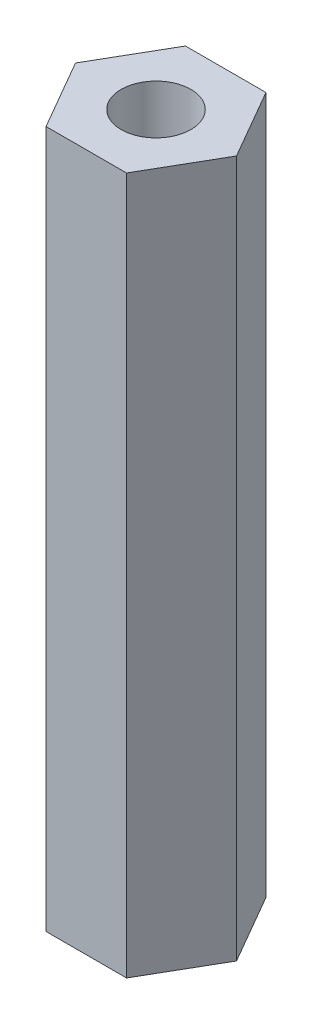
SolidWorks part; units mm, degrees
ref_plane "Front Plane" through (0, 0, 0) normal (0, 0, 1) x (1, 0, 0)
ref_plane "Top Plane" through (0, 0, 0) normal (0, 1, 0) x (1, 0, 0)
ref_plane "Right Plane" through (0, 0, 0) normal (1, 0, 0) x (0, 0, -1)
sketch "Sketch1" plane through (0, 0, 0) normal (0, 1, 0) x (1, 0, 0)
  line L1 (1.7321, 3) -> (-1.7321, 3)
  line L2 (-1.7321, 3) -> (-3.4641, 0)
  line L3 (-3.4641, 0) -> (-1.7321, -3)
  line L4 (-1.7321, -3) -> (1.7321, -3)
  line L5 (1.7321, -3) -> (3.4641, 0)
  line L6 (3.4641, 0) -> (1.7321, 3)
  circle A0 centre (0, 0) radius 3 construction
  circle A1 centre (0, 0) radius 1.5
  dimension "D2" = 3
  dimension "D1" = 6
extrude "Boss-Extrude1" add sketch "Sketch1" along normal blind 30
